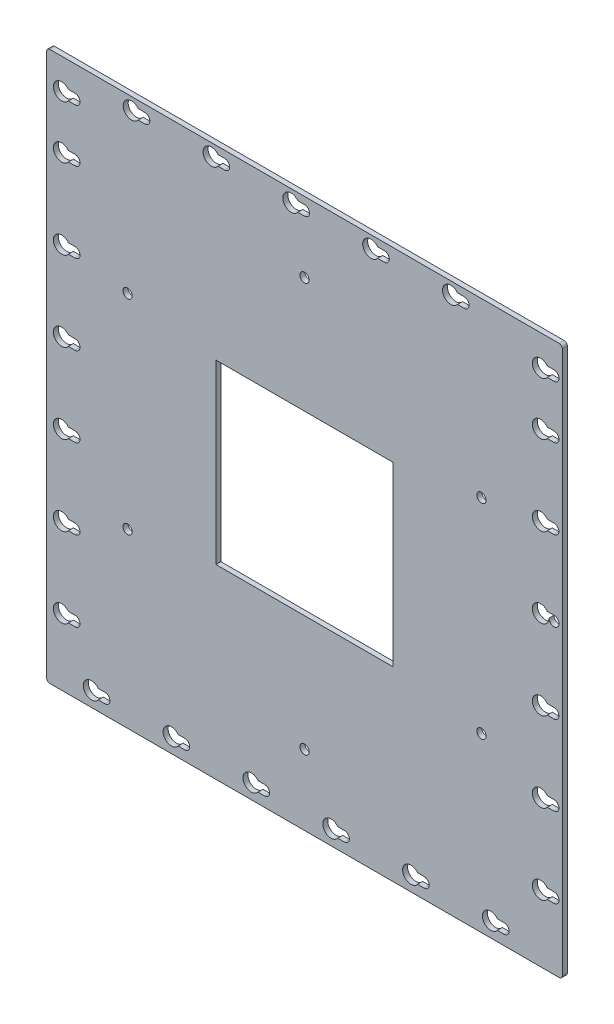
SolidWorks part; units mm, degrees
material "6061 Alloy"
ref_plane "Front Plane" through (0, 0, 0) normal (0, 0, 1) x (1, 0, 0)
ref_plane "Top Plane" through (0, 0, 0) normal (0, 1, 0) x (1, 0, 0)
ref_plane "Right Plane" through (0, 0, 0) normal (1, 0, 0) x (0, 0, -1)
sketch "Sketch1" plane through (0, 0, 0) normal (0, 0, 1) x (1, 0, 0)
  line L0 (0, 0) -> (0, -174.745)
  line L3 (0, -174.745) -> (165.1, -174.745)
  line L5 (0, 0) -> (165.1, 0)
  line L6 (165.1, -174.745) -> (165.1, 0)
  line L7 (82.55, 0) -> (82.55, -174.745) construction
  line L8 (31.75, -2.2625) -> (29.6344, -2.2625)
  line L9 (31.75, -5.4375) -> (29.6344, -5.4375)
  line L10 (9.525, -24.9325) -> (7.4094, -24.9325)
  line L11 (9.525, -28.1075) -> (7.4094, -28.1075)
  line L12 (161.925, -24.9325) -> (159.8094, -24.9325)
  line L13 (161.925, -28.1075) -> (159.8094, -28.1075)
  line L14 (57.15, -2.2625) -> (55.0344, -2.2625)
  line L15 (57.15, -5.4375) -> (55.0344, -5.4375)
  line L16 (82.55, -2.2625) -> (80.4344, -2.2625)
  line L17 (82.55, -5.4375) -> (80.4344, -5.4375)
  line L18 (107.95, -2.2625) -> (105.8344, -2.2625)
  line L19 (107.95, -5.4375) -> (105.8344, -5.4375)
  line L20 (133.35, -2.2625) -> (131.2344, -2.2625)
  line L21 (133.35, -5.4375) -> (131.2344, -5.4375)
  line L22 (9.525, -50.3325) -> (7.4094, -50.3325)
  line L23 (9.525, -53.5075) -> (7.4094, -53.5075)
  line L24 (161.925, -50.3325) -> (159.8094, -50.3325)
  line L25 (161.925, -53.5075) -> (159.8094, -53.5075)
  line L26 (9.525, -75.7325) -> (7.4094, -75.7325)
  line L27 (9.525, -78.9075) -> (7.4094, -78.9075)
  line L28 (161.925, -75.7325) -> (159.8094, -75.7325)
  line L29 (161.925, -78.9075) -> (159.8094, -78.9075)
  line L30 (9.525, -101.1325) -> (7.4094, -101.1325)
  line L31 (9.525, -104.3075) -> (7.4094, -104.3075)
  line L32 (161.925, -101.1325) -> (159.8094, -101.1325)
  line L33 (161.925, -104.3075) -> (159.8094, -104.3075)
  line L34 (9.525, -126.5325) -> (7.4094, -126.5325)
  line L35 (9.525, -129.7075) -> (7.4094, -129.7075)
  line L36 (161.925, -126.5325) -> (159.8094, -126.5325)
  line L37 (161.925, -129.7075) -> (159.8094, -129.7075)
  line L38 (9.525, -151.9325) -> (7.4094, -151.9325)
  line L39 (9.525, -155.1075) -> (7.4094, -155.1075)
  line L40 (161.925, -151.9325) -> (159.8094, -151.9325)
  line L41 (161.925, -155.1075) -> (159.8094, -155.1075)
  line L42 (19.05, -168.395) -> (16.9344, -168.395)
  line L43 (19.05, -171.57) -> (16.9344, -171.57)
  line L44 (44.45, -168.395) -> (42.3344, -168.395)
  line L45 (44.45, -171.57) -> (42.3344, -171.57)
  line L46 (69.85, -168.395) -> (67.7344, -168.395)
  line L47 (69.85, -171.57) -> (67.7344, -171.57)
  line L48 (95.25, -168.395) -> (93.1344, -168.395)
  line L49 (95.25, -171.57) -> (93.1344, -171.57)
  line L50 (120.65, -168.395) -> (118.5344, -168.395)
  line L51 (120.65, -171.57) -> (118.5344, -171.57)
  line L52 (146.05, -168.395) -> (143.9344, -168.395)
  line L53 (146.05, -171.57) -> (143.9344, -171.57)
  line L54 (0.5, 0) -> (0.5, -174.745)
  line L55 (164.6, -174.745) -> (164.6, 0)
  line L56 (0.5, -174.745) -> (164.6, -174.745)
  line L57 (9.525, -8.1) -> (7.4094, -8.1)
  line L58 (9.525, -11.275) -> (7.4094, -11.275)
  line L59 (161.925, -8.1) -> (159.8094, -8.1)
  line L60 (161.925, -11.275) -> (159.8094, -11.275)
  line L62 (54.375, -59.1975) -> (110.725, -59.1975)
  line L63 (54.375, -59.1975) -> (54.375, -115.5475)
  line L64 (54.375, -115.5475) -> (110.725, -115.5475)
  line L65 (110.725, -59.1975) -> (110.725, -115.5475)
  line L66 (54.375, -59.1975) -> (110.725, -115.5475) construction
  line L67 (54.375, -115.5475) -> (110.725, -59.1975) construction
  circle A41 centre (9.525, -153.52) radius 1.5875
  circle A42 centre (19.05, -169.9825) radius 1.5875
  circle A43 centre (9.525, -128.12) radius 1.5875
  circle A44 centre (9.525, -102.72) radius 1.5875
  circle A45 centre (9.525, -77.32) radius 1.5875
  circle A46 centre (9.525, -51.92) radius 1.5875
  circle A47 centre (9.525, -26.52) radius 1.5875
  circle A49 centre (44.45, -169.9825) radius 1.5875
  circle A50 centre (69.85, -169.9825) radius 1.5875
  circle A51 centre (95.25, -169.9825) radius 1.5875
  circle A52 centre (120.65, -169.9825) radius 1.5875
  circle A68 centre (146.05, -169.9825) radius 1.5875
  circle A69 centre (107.95, -3.85) radius 1.5875
  circle A70 centre (82.55, -3.85) radius 1.5875
  circle A71 centre (57.15, -3.85) radius 1.5875
  circle A72 centre (9.525, -1.12) radius 1.5875 [skipped]
  circle A73 centre (133.35, -3.85) radius 1.5875
  circle A74 centre (31.75, -3.85) radius 1.5875
  circle A75 centre (161.925, -26.52) radius 1.5875
  circle A76 centre (161.925, -51.92) radius 1.5875
  circle A77 centre (161.925, -77.32) radius 1.5875
  circle A78 centre (161.925, -102.72) radius 1.5875
  circle A79 centre (161.925, -128.12) radius 1.5875
  circle A80 centre (161.925, -153.52) radius 1.5875
  circle A81 centre (27.5125, -3.85) radius 2.65
  circle A83 centre (5.2875, -26.52) radius 2.65
  circle A84 centre (157.6875, -26.52) radius 2.65
  circle A85 centre (52.9125, -3.85) radius 2.65
  circle A86 centre (78.3125, -3.85) radius 2.65
  circle A87 centre (103.7125, -3.85) radius 2.65
  circle A88 centre (129.1125, -3.85) radius 2.65
  circle A89 centre (5.2875, -51.92) radius 2.65
  circle A90 centre (157.6875, -51.92) radius 2.65
  circle A91 centre (5.2875, -77.32) radius 2.65
  circle A92 centre (157.6875, -77.32) radius 2.65
  circle A93 centre (5.2875, -102.72) radius 2.65
  circle A94 centre (157.6875, -102.72) radius 2.65
  circle A95 centre (5.2875, -128.12) radius 2.65
  circle A96 centre (157.6875, -128.12) radius 2.65
  circle A97 centre (5.2875, -153.52) radius 2.65
  circle A98 centre (157.6875, -153.52) radius 2.65
  circle A99 centre (14.8125, -169.9825) radius 2.65
  circle A100 centre (40.2125, -169.9825) radius 2.65
  circle A101 centre (65.6125, -169.9825) radius 2.65
  circle A102 centre (91.0125, -169.9825) radius 2.65
  circle A103 centre (116.4125, -169.9825) radius 2.65
  circle A104 centre (141.8125, -169.9825) radius 2.65
  circle A105 centre (82.55, -87.3725) radius 2.5527
  circle A107 centre (9.525, -9.6875) radius 1.5875
  circle A108 centre (5.2875, -9.6875) radius 2.65
  circle A109 centre (161.925, -9.6875) radius 1.5875
  circle A110 centre (157.6875, -9.6875) radius 2.65
  circle A111 centre (82.55, -22.3725) radius 1.4732
  circle A112 centre (138.8417, -54.8725) radius 1.4732
  circle A113 centre (138.8417, -119.8725) radius 1.4732
  circle A114 centre (82.55, -152.3725) radius 1.4732
  circle A115 centre (26.2583, -119.8725) radius 1.4732
  circle A116 centre (26.2583, -54.8725) radius 1.4732
  point P233 (82.55, -87.3725)
  dimension "D3" = 3.175
  dimension "D8" = 3.175
  dimension "D21" = 5.3
  dimension "D31" = 5.1054
  dimension "D33" = 5.3
  dimension "D36" = 2.9464
  dimension "D1" = 165.1
  dimension "D2" = 174.745
  dimension "D5" = 9.525
  dimension "D4" = 21.225
  dimension "D6" = 19.05
  dimension "D7" = 4.7625
  dimension "D9" = 25.4
  dimension "D10" = 25.4
  dimension "D15" = 25.4
  dimension "D12" = 3.85
  dimension "D13" = 31.75
  dimension "D17" = 31.75
  dimension "D18" = 3.175
  dimension "D20" = 25.4
  dimension "D23" = 25.4
  dimension "D25" = 25.4
  dimension "D27" = 25.4
  dimension "D28" = 0.5
  dimension "D29" = 0.5
  dimension "D30" = 87.3725
  dimension "D34" = 16.8325
  dimension "D35" = 5.8375
  dimension "D32" = 56.35
  dimension "D37" = 65
  dimension "D39" = 65
  dimension "D11" = 7
  dimension "D14" = 5
  dimension "D16" = 5
  dimension "D19" = 6
  dimension "D22" = 5
  dimension "D24" = 6
  dimension "D26" = 6
  dimension "D38" = 6
extrude "Boss-Extrude1" add sketch "Sketch1" along normal blind 1.5875 contours L7 L5 L0 L3 A50 A41 A42 A43 A44 A45 A46 A47 A73 A49 | L5 L7 A70 A105 L56 L55 A84 L12 A75 L13 A87 L18 A69 L19 A88 L20 A73 L21 A90 L24 A76 L25 A92 L28 A77 L29 A94 L32 A78 L33 A96 L36 A79 L37 A98 L40 A80 L41 A102 L48
fillet "Fillet1" radius 1 4 edges at (164.6, 0, 0.7937) (164.6, -174.745, 0.7937) (0.5, -174.745, 0.7937) (0.5, 0, 0.7937)
equation "\"D8@Sketch1\"=\"D3@Sketch1\""
equation "\"D29@Sketch1\"=\"D28@Sketch1\""
equation "\"D30@Sketch1\"=\"D2@Sketch1\"/2"
